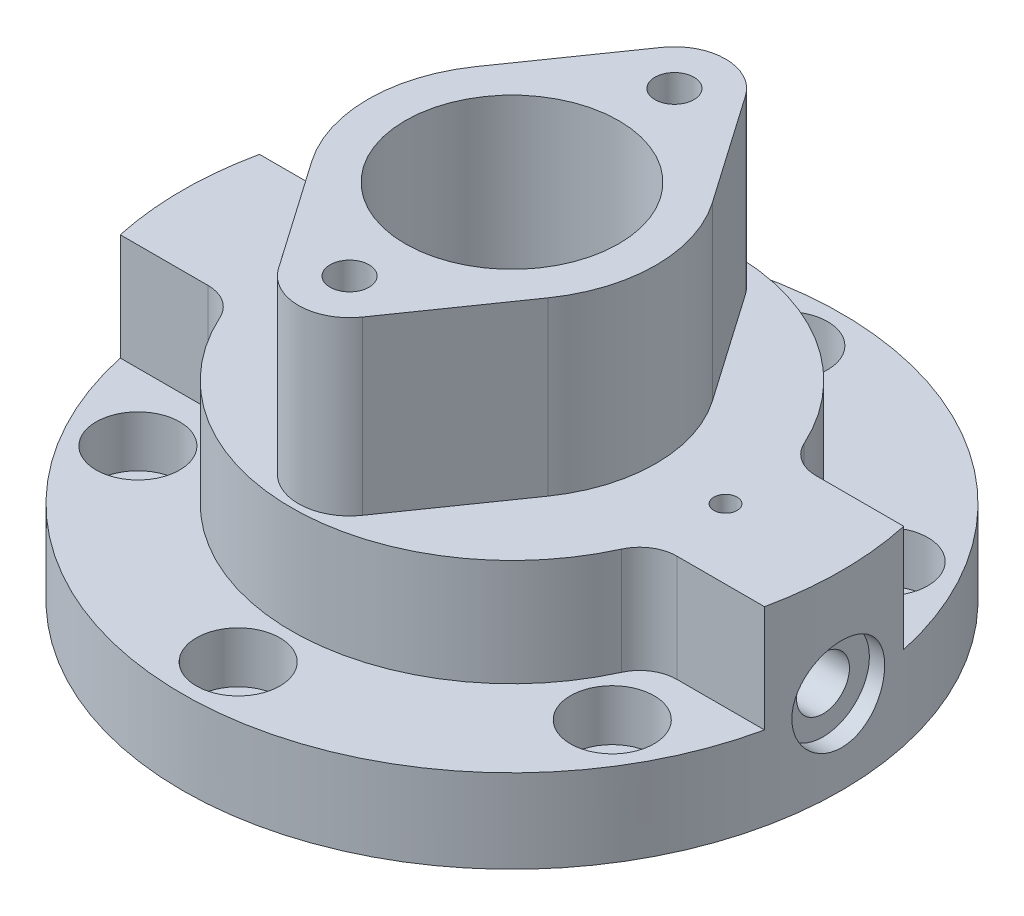
SolidWorks part; units mm, degrees
ref_plane "정면" through (0, 0, 0) normal (0, 0, 1) x (1, 0, 0)
ref_plane "윗면" through (0, 0, 0) normal (0, 1, 0) x (1, 0, 0)
ref_plane "우측면" through (0, 0, 0) normal (1, 0, 0) x (0, 0, -1)
sketch "스케치1" plane through (0, 0, 0) normal (0, 1, 0) x (1, 0, 0)
  line L0 (0, 0) -> (0, 46.3284) construction
  circle A0 centre (0, 0) radius 35.5
  circle A1 centre (0, 29.5) radius 2.75
  circle A2 centre (25.5477, 14.75) radius 2.75
  circle A3 centre (25.5477, -14.75) radius 2.75
  circle A4 centre (0, -29.5) radius 2.75
  circle A5 centre (-25.5477, -14.75) radius 2.75
  circle A6 centre (-25.5477, 14.75) radius 2.75
  point P18 (0, 0)
  dimension "D1" = 71
  dimension "D2" = 5.5
  dimension "D3" = 29.5
  dimension "D4" = 6
extrude "보스-돌출1" add sketch "스케치1" along normal blind 9
sketch "스케치2" plane through (0, 9, 0) normal (0, 1, 0) x (1, 0, 0)
  line L0 (0, 0) -> (0, 38.1297) construction
  circle A0 centre (0, 29.5) radius 4.5
  circle A2 centre (25.5482, 14.7509) radius 4.5
  circle A3 centre (25.5492, -14.7491) radius 4.5
  circle A4 centre (0.002, -29.5) radius 4.5
  circle A5 centre (-25.5462, -14.7509) radius 4.5
  circle A6 centre (-25.5472, 14.7491) radius 4.5
  point P20 (0.001, 0)
  dimension "D1" = 9
  dimension "D2" = 6
extrude "컷-돌출1" cut sketch "스케치2" against normal blind 5.5
sketch "스케치3" plane through (0, 9, 0) normal (0, 1, 0) x (1, 0, 0)
  line L0 (23.75, 0) -> (47.4377, 0) construction
  line L1 (47.4377, 0) -> (23.75, 0) construction
  line L2 (0, 23.75) -> (0, 37.5627) construction
  line L3 (34.6987, 7.5) -> (22.5347, 7.5)
  line L4 (34.6987, -7.5) -> (22.5347, -7.5)
  line L5 (34.6987, 7.5) -> (22.5347, 7.5)
  line L6 (34.6987, -7.5) -> (22.5347, -7.5)
  line L7 (-34.6987, -7.5) -> (-22.5347, -7.5)
  line L8 (-34.6987, 7.5) -> (-22.5347, 7.5)
  arc A0 (-22.5347, -7.5) -> (22.5347, -7.5) centre (0, 0) ccw
  circle A1 centre (0, 0) radius 35.5 construction
  arc A2 (-34.6987, 7.5) -> (-34.6987, -7.5) centre (0, 0) ccw
  arc A3 (34.6987, -7.5) -> (34.6987, 7.5) centre (0, 0) ccw
  arc A4 (22.5347, 7.5) -> (-22.5347, 7.5) centre (0, 0) ccw
  point P15 (-28.6167, 7.5)
  circle M13 centre (0, 0) radius 35.5
  dimension "D1" = 47.5
  dimension "D2" = 15
extrude "보스-돌출2" add sketch "스케치3" along normal blind 11.5 contours L3 A4 L8 L7 A0 L4 M13
fillet "필렛1" radius 4 4 edges at (-22.5347, 14.75, -7.5) (22.5347, 14.75, -7.5) (-22.5347, 14.75, 7.5) (22.5347, 14.75, 7.5)
sketch "스케치8" plane through (0, 20.5, 0) normal (0, 1, 0) x (1, 0, 0)
  line L0 (0, 0) -> (0, 37.4682) construction
  line L1 (0, 0) -> (43.2798, 0) construction
  line L2 (-4.5136, 20.6429) -> (-12.7201, 8.8571)
  line L3 (4.5136, 20.6429) -> (12.7201, 8.8571)
  line L4 (4.5136, -20.6429) -> (12.7201, -8.8571)
  line L5 (-4.5136, -20.6429) -> (-12.7201, -8.8571)
  arc A0 (-12.7201, 8.8571) -> (-12.7201, -8.8571) centre (0, 0) ccw
  arc A1 (4.5136, 20.6429) -> (-4.5136, 20.6429) centre (0, 17.5) ccw
  arc A2 (4.5136, -20.6429) -> (-4.5136, -20.6429) centre (0, -17.5) cw
  arc A3 (12.7201, -8.8571) -> (12.7201, 8.8571) centre (0, 0) ccw
  circle A5 centre (0, -29.5) radius 2.75 construction
  dimension "D1" = 47
  dimension "D2" = 5.5
  dimension "D3" = 15.5
extrude "보스-돌출3" add sketch "스케치8" along normal blind 18.5
sketch "스케치10" plane through (0, 0, 0) normal (0, 0, 1) x (1, 0, 0)
  line L0 (0, 0) -> (0, 48.5257) construction
  line L1 (11.5, 39) -> (11.5, 20.5)
  line L2 (4.5136, 39) -> (12.7201, 39) construction
  line L3 (21.6146, 20.5) -> (-21.6146, 20.5) construction
  line L4 (11.5, 20.5) -> (7.5, 20.5)
  line L5 (7.5, 20.5) -> (7.5, 0)
  line L6 (-35.5, 0) -> (35.5, 0) construction
  line L7 (7.5, 0) -> (0, 0)
  line L8 (0, 0) -> (0, 39)
  line L10 (11.5, 39) -> (0, 39)
  line L11 (4.5136, 39) -> (-4.5136, 39) construction
  dimension "D1" = 11.5
  dimension "D2" = 7.5
  dimension "D3" = 7.5
hole_wizard "M5 나사 구멍1" positions "스케치11" profile "스케치12" tap size "M5" standard "ISO"
sketch "스케치11" plane through (0, 39, 0) normal (0, 1, 0) x (1, 0, 0)
  line L0 (0, 0) -> (23.1186, 0) construction
  circle A0 centre (0, -29.5) radius 2.75 construction
  point P0 (0, 17.5)
  point P8 (0, -17.5)
  dimension "D1" = 47
sketch "스케치12" plane through (0, 39, -17.5) normal (1, 0, 0) x (0, 0, 1)
  line L0 (0, 0) -> (0, 8.7618)
  line L1 (0, 8.7618) -> (2.1, 7.5)
  line L2 (2.1, 7.5) -> (2.1, 0)
  line L5 (2.1, 0) -> (0, 0)
  line L10 (0, 8.7618) -> (-2.1, 7.5) construction
  line L11 (0, -6.35) -> (0, 107.95) construction
  dimension "탭 드릴 지름" = 4.2
  dimension "탭 드릴 깊이" = 7.5
  dimension "드릴 각도" = 118
cosmetic thread "구멍 나사산1" parameters "D1"=7.5, "D2"=5
cosmetic thread "구멍 나사산2" parameters "D1"=7.5, "D2"=5
sketch "스케치13" plane through (0, 0, 0) normal (1, 0, 0) x (0, 0, -1)
  line L0 (0, 0) -> (0, 48.5257) construction
  line L1 (-35.5, 0) -> (35.5, 0) construction
  circle A0 centre (0, 9) radius 2.85
  dimension "D1" = 5.7
  dimension "D2" = 9
extrude "컷-돌출3" cut sketch "스케치13" against normal through all both and the other way through all
ref_plane "평면1" through (33.5, 0, 0) normal (1, 0, 0) x (0, 0, -1)
sketch "스케치14" plane through (33.5, 0, 0) normal (1, 0, 0) x (0, 0, -1)
  circle A0 centre (0, 9) radius 5
  dimension "D1" = 10
extrude "컷-돌출4" cut sketch "스케치14" along normal through all
ref_plane "평면2" through (-33.5, 0, 0) normal (1, 0, 0) x (0, 0, -1)
sketch "스케치15" plane through (-33.5, 0, 0) normal (1, 0, 0) x (0, 0, -1)
  circle A1 centre (0, 9) radius 5
  dimension "D1" = 10
extrude "컷-돌출5" cut sketch "스케치15" against normal through all
hole_wizard "Ø2.5 (2.5) 지름 구멍1" positions "스케치16" profile "스케치17" hole size "Ø2.5" standard "ISO"
sketch "스케치16" plane through (0, 20.5, 0) normal (0, 1, 0) x (1, 0, 0)
  line L0 (0, 0) -> (0, 49.5555) construction
  line L2 (0, 0) -> (57.386, 0) construction
  point P0 (23, 0)
  point P9 (-23, 0)
  dimension "D1" = 46
sketch "스케치17" plane through (23, 20.5, 0) normal (1, 0, 0) x (0, 0, 1)
  line L0 (0, 0) -> (0, 8.65)
  line L1 (0, 8.65) -> (1.25, 8.65)
  line L2 (1.25, 8.65) -> (1.25, 0)
  line L5 (1.25, 0) -> (0, 0)
  line L11 (0, -6.35) -> (0, 107.95) construction
  dimension "관통 구멍 지름" = 2.5
  dimension "관통 구멍 깊이" = 8.65
revolve "컷-회전1" cut sketch "스케치10" angle 360 about L0
ref_plane "평면3" through (0, 9, 0) normal (0, -1, 0) x (-1, 0, 0)
sketch "스케치19" plane through (0, 9, 0) normal (0, -1, 0) x (-1, 0, 0)
  circle A0 centre (0, 0) radius 12.5
  dimension "D1" = 25
extrude "컷-돌출6" cut sketch "스케치19" against normal blind 7 draft 15
sketch "스케치20" plane through (0, 0, 0) normal (0, -1, 0) x (1, 0, 0)
  circle A0 centre (0, 0) radius 15.5
  dimension "D1" = 31
extrude "컷-돌출7" cut sketch "스케치20" against normal blind 9
fillet "필렛2" radius 2 1 edges at (0, 16, -10.6244)
